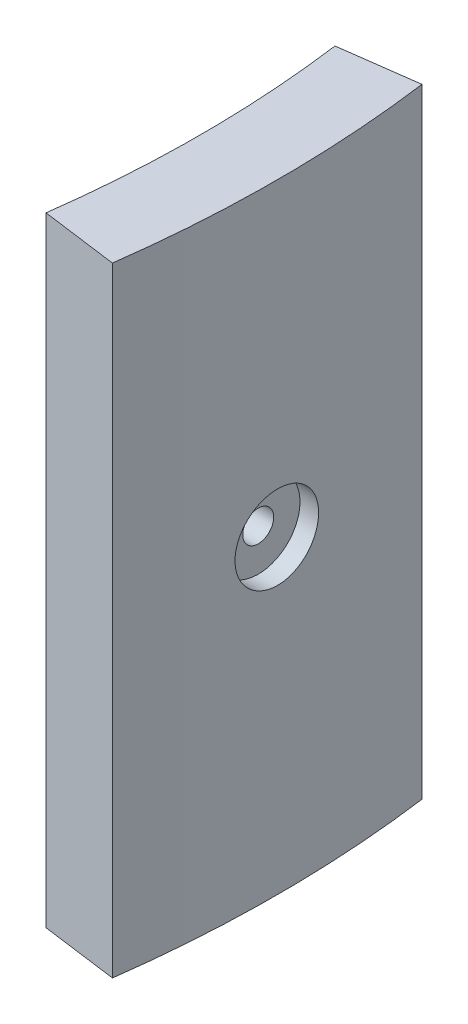
SolidWorks part; units mm, degrees
ref_plane "Front Plane" through (0, 0, 0) normal (0, 0, 1) x (1, 0, 0)
ref_plane "Top Plane" through (0, 0, 0) normal (0, 1, 0) x (1, 0, 0)
ref_plane "Right Plane" through (0, 0, 0) normal (1, 0, 0) x (0, 0, -1)
sketch "Sketch4" plane through (0, 0, 0) normal (0, 1, 0) x (1, 0, 0)
  line L0 (94.3995, 12.7) -> (88.1062, 11.8533)
  line L1 (94.3995, -12.7) -> (88.1062, -11.8533)
  arc A0 (88.1062, -11.8533) -> (88.1062, 11.8533) centre (0, 0) ccw
  arc A1 (94.3995, -12.7) -> (94.3995, 12.7) centre (0, 0) ccw
  point P1 (81.1602, 46.7258)
  point P3 (84.3127, -40.7633)
  point P8 (87.8697, -11.1839)
  point P9 (88.9, 0)
  point P10 (92.7847, -12.0559)
  dimension "D1" = 177.8
  dimension "D2" = 190.5
  dimension "D3" = 25.4
extrude "Boss-Extrude1" add sketch "Sketch4" along normal mid plane 50.8
ref_plane "Plane1" through (95.25, 25.4, 0) normal (1, 0, 0) x (0, 0, -1)
sketch "Sketch5" plane through (95.25, 25.4, 0) normal (1, 0, 0) x (0, 0, -1)
  circle A0 centre (0, -25.4) radius 3.429
  dimension "D1" = 6.858
extrude "Cut-Extrude1" cut sketch "Sketch5" against normal blind 1.5875
sketch "Sketch6" plane through (93.6625, 0, 0) normal (1, 0, 0) x (0, 0, -1)
  circle A0 centre (0, 0) radius 1.27
  dimension "D1" = 2.54
extrude "Cut-Extrude2" cut sketch "Sketch6" against normal through all
